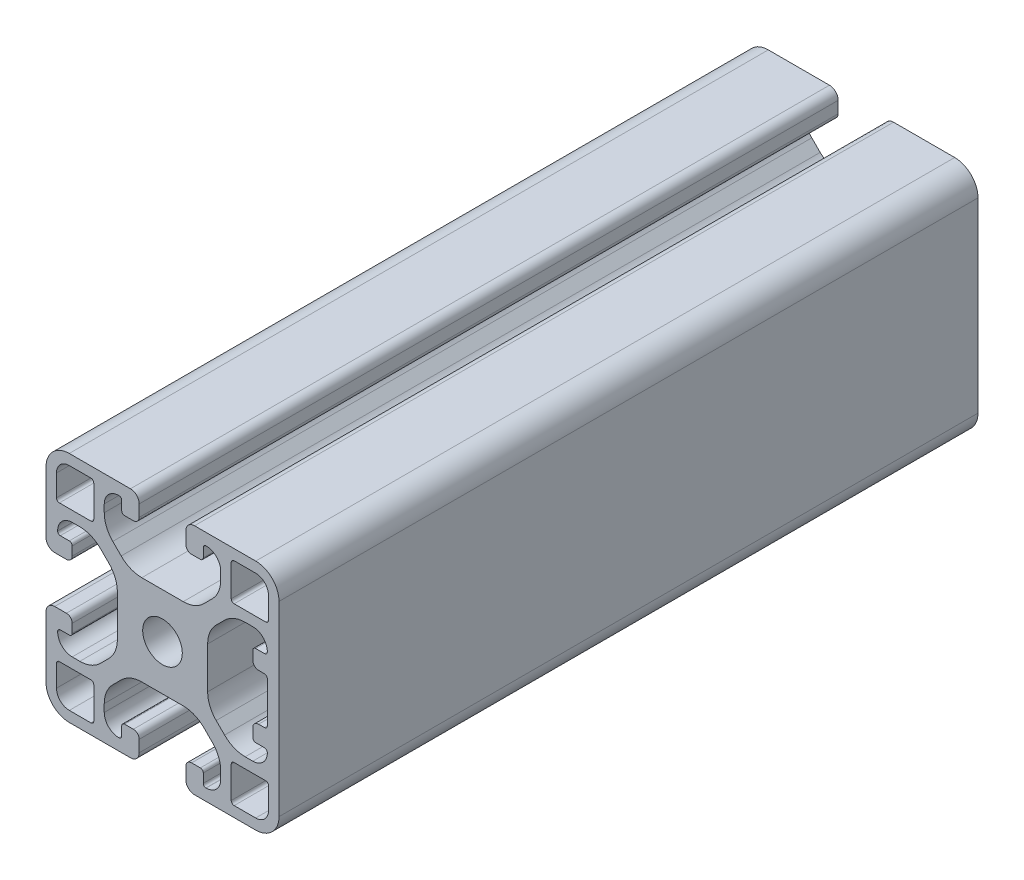
SolidWorks part; units mm, degrees
ref_plane "Piano frontale" through (0, 0, 0) normal (0, 0, 1) x (1, 0, 0)
ref_plane "Piano superiore" through (0, 0, 0) normal (0, 1, 0) x (1, 0, 0)
ref_plane "Piano destro" through (0, 0, 0) normal (1, 0, 0) x (0, 0, -1)
ref_plane "Piano1" through (0, 0, -340) normal (0, 0, -1) x (-1, 0, 0)
sketch "Schizzo1" plane through (0, 0, -340) normal (0, 0, -1) x (-1, 0, 0)
  line L0 (-12.3, -18.2) -> (-16, -18.2)
  line L1 (-18.2, -16) -> (-18.2, -12.3)
  line L2 (-17.7, -11.8) -> (-12.3, -11.8)
  line L3 (-11.8, -12.3) -> (-11.8, -17.7)
  line L4 (-11.8, 17.7) -> (-11.8, 12.3)
  line L5 (-12.3, 11.8) -> (-17.7, 11.8)
  line L6 (-18.2, 12.3) -> (-18.2, 16)
  line L7 (-16, 18.2) -> (-12.3, 18.2)
  line L8 (18.2, 16) -> (18.2, 12.3)
  line L9 (17.7, 11.8) -> (12.3, 11.8)
  line L10 (11.8, 12.3) -> (11.8, 17.7)
  line L11 (12.3, 18.2) -> (16, 18.2)
  line L12 (6.5, -15.5) -> (5, -15.5)
  line L13 (4, -16.5) -> (4, -18.5)
  line L14 (5.5, -20) -> (16, -20)
  line L15 (20, -16) -> (20, -5.5)
  line L16 (18.5, -4) -> (16.5, -4)
  line L17 (15.5, -5) -> (15.5, -6.5)
  line L18 (16, -7) -> (17.55, -7)
  line L19 (18, -7.45) -> (18, -7.5)
  line L20 (15.5, -10) -> (14.1924, -10)
  line L21 (10.6569, -8.5355) -> (9.2145, -7.0931)
  line L22 (7.75, -3.5576) -> (7.75, 3.5576)
  line L23 (9.2145, 7.0931) -> (10.6569, 8.5355)
  line L24 (14.1924, 10) -> (15.5, 10)
  line L25 (18, 7.5) -> (18, 7.45)
  line L26 (17.55, 7) -> (16, 7)
  line L27 (15.5, 6.5) -> (15.5, 5)
  line L28 (16.5, 4) -> (18.5, 4)
  line L29 (20, 5.5) -> (20, 16)
  line L30 (16, 20) -> (5.5, 20)
  line L31 (4, 18.5) -> (4, 16.5)
  line L32 (5, 15.5) -> (6.5, 15.5)
  line L33 (7, 16) -> (7, 17.55)
  line L34 (7.45, 18) -> (7.5, 18)
  line L35 (10, 15.5) -> (10, 14.1924)
  line L36 (8.5355, 10.6569) -> (7.0931, 9.2145)
  line L37 (3.5576, 7.75) -> (-3.5576, 7.75)
  line L38 (-7.0931, 9.2145) -> (-8.5355, 10.6569)
  line L39 (-10, 14.1924) -> (-10, 15.5)
  line L40 (-7.5, 18) -> (-7.45, 18)
  line L41 (-7, 17.55) -> (-7, 16)
  line L42 (-6.5, 15.5) -> (-5, 15.5)
  line L43 (-4, 16.5) -> (-4, 18.5)
  line L44 (-5.5, 20) -> (-16, 20)
  line L45 (-20, 16) -> (-20, -16)
  line L46 (-16, -20) -> (-5.5, -20)
  line L47 (-4, -18.5) -> (-4, -16.5)
  line L48 (-5, -15.5) -> (-6.5, -15.5)
  line L49 (-7, -16) -> (-7, -17.55)
  line L50 (-7.45, -18) -> (-7.5, -18)
  line L51 (-10, -15.5) -> (-10, -14.1924)
  line L52 (-8.5355, -10.6569) -> (-7.0931, -9.2145)
  line L53 (-3.5576, -7.75) -> (3.5576, -7.75)
  line L54 (7.0931, -9.2145) -> (8.5355, -10.6569)
  line L55 (10, -14.1924) -> (10, -15.5)
  line L56 (7.5, -18) -> (7.45, -18)
  line L57 (7, -17.55) -> (7, -16)
  line L58 (18.2, -12.3) -> (18.2, -16)
  line L59 (16, -18.2) -> (12.3, -18.2)
  line L60 (11.8, -17.7) -> (11.8, -12.3)
  line L61 (12.3, -11.8) -> (17.7, -11.8)
  line L62 (-16, 7) -> (-17.5, 7)
  line L63 (-15.5, 10) -> (-14.1924, 10)
  line L64 (-10.6569, 8.5355) -> (-9.2145, 7.0931)
  line L65 (-7.75, 3.5576) -> (-7.75, -3.5576)
  line L66 (-9.2145, -7.0931) -> (-10.6569, -8.5355)
  line L67 (-14.1924, -10) -> (-15.5, -10)
  line L68 (-17.5, -7) -> (-16, -7)
  line L69 (-15.5, -6.5) -> (-15.5, -5)
  line L70 (-16.5, -4) -> (-17.5, -4)
  line L71 (-18, -3.5) -> (-18, 3.5)
  line L72 (-17.5, 4) -> (-16.5, 4)
  line L73 (-15.5, 5) -> (-15.5, 6.5)
  arc A0 (-16, -18.2) -> (-18.2, -16) centre (-16, -16) cw
  arc A1 (-18.2, -12.3) -> (-17.7, -11.8) centre (-17.7, -12.3) cw
  arc A2 (-12.3, -11.8) -> (-11.8, -12.3) centre (-12.3, -12.3) cw
  arc A3 (-11.8, -17.7) -> (-12.3, -18.2) centre (-12.3, -17.7) cw
  arc A4 (-12.3, 18.2) -> (-11.8, 17.7) centre (-12.3, 17.7) cw
  arc A5 (-11.8, 12.3) -> (-12.3, 11.8) centre (-12.3, 12.3) cw
  arc A6 (-17.7, 11.8) -> (-18.2, 12.3) centre (-17.7, 12.3) cw
  arc A7 (-18.2, 16) -> (-16, 18.2) centre (-16, 16) cw
  arc A8 (16, 18.2) -> (18.2, 16) centre (16, 16) cw
  arc A9 (18.2, 12.3) -> (17.7, 11.8) centre (17.7, 12.3) cw
  arc A10 (12.3, 11.8) -> (11.8, 12.3) centre (12.3, 12.3) cw
  arc A11 (11.8, 17.7) -> (12.3, 18.2) centre (12.3, 17.7) cw
  arc A12 (5, -15.5) -> (4, -16.5) centre (5, -16.5) ccw
  arc A13 (4, -18.5) -> (5.5, -20) centre (5.5, -18.5) ccw
  arc A14 (16, -20) -> (20, -16) centre (16, -16) ccw
  arc A15 (20, -5.5) -> (18.5, -4) centre (18.5, -5.5) ccw
  arc A16 (16.5, -4) -> (15.5, -5) centre (16.5, -5) ccw
  arc A17 (15.5, -6.5) -> (16, -7) centre (16, -6.5) ccw
  arc A18 (17.55, -7) -> (18, -7.45) centre (17.55, -7.45) cw
  arc A19 (18, -7.5) -> (15.5, -10) centre (15.5, -7.5) cw
  arc A20 (14.1924, -10) -> (10.6569, -8.5355) centre (14.1924, -5) cw
  arc A21 (9.2145, -7.0931) -> (7.75, -3.5576) centre (12.75, -3.5576) cw
  arc A22 (7.75, 3.5576) -> (9.2145, 7.0931) centre (12.75, 3.5576) cw
  arc A23 (10.6569, 8.5355) -> (14.1924, 10) centre (14.1924, 5) cw
  arc A24 (15.5, 10) -> (18, 7.5) centre (15.5, 7.5) cw
  arc A25 (18, 7.45) -> (17.55, 7) centre (17.55, 7.45) cw
  arc A26 (16, 7) -> (15.5, 6.5) centre (16, 6.5) ccw
  arc A27 (15.5, 5) -> (16.5, 4) centre (16.5, 5) ccw
  arc A28 (18.5, 4) -> (20, 5.5) centre (18.5, 5.5) ccw
  arc A29 (20, 16) -> (16, 20) centre (16, 16) ccw
  arc A30 (5.5, 20) -> (4, 18.5) centre (5.5, 18.5) ccw
  arc A31 (4, 16.5) -> (5, 15.5) centre (5, 16.5) ccw
  arc A32 (6.5, 15.5) -> (7, 16) centre (6.5, 16) ccw
  arc A33 (7, 17.55) -> (7.45, 18) centre (7.45, 17.55) cw
  arc A34 (7.5, 18) -> (10, 15.5) centre (7.5, 15.5) cw
  arc A35 (10, 14.1924) -> (8.5355, 10.6569) centre (5, 14.1924) cw
  arc A36 (7.0931, 9.2145) -> (3.5576, 7.75) centre (3.5576, 12.75) cw
  arc A37 (-3.5576, 7.75) -> (-7.0931, 9.2145) centre (-3.5576, 12.75) cw
  arc A38 (-8.5355, 10.6569) -> (-10, 14.1924) centre (-5, 14.1924) cw
  arc A39 (-10, 15.5) -> (-7.5, 18) centre (-7.5, 15.5) cw
  arc A40 (-7.45, 18) -> (-7, 17.55) centre (-7.45, 17.55) cw
  arc A41 (-7, 16) -> (-6.5, 15.5) centre (-6.5, 16) ccw
  arc A42 (-5, 15.5) -> (-4, 16.5) centre (-5, 16.5) ccw
  arc A43 (-4, 18.5) -> (-5.5, 20) centre (-5.5, 18.5) ccw
  arc A44 (-16, 20) -> (-20, 16) centre (-16, 16) ccw
  arc A45 (-20, -16) -> (-16, -20) centre (-16, -16) ccw
  arc A46 (-5.5, -20) -> (-4, -18.5) centre (-5.5, -18.5) ccw
  arc A47 (-4, -16.5) -> (-5, -15.5) centre (-5, -16.5) ccw
  arc A48 (-6.5, -15.5) -> (-7, -16) centre (-6.5, -16) ccw
  arc A49 (-7, -17.55) -> (-7.45, -18) centre (-7.45, -17.55) cw
  arc A50 (-7.5, -18) -> (-10, -15.5) centre (-7.5, -15.5) cw
  arc A51 (-10, -14.1924) -> (-8.5355, -10.6569) centre (-5, -14.1924) cw
  arc A52 (-7.0931, -9.2145) -> (-3.5576, -7.75) centre (-3.5576, -12.75) cw
  arc A53 (3.5576, -7.75) -> (7.0931, -9.2145) centre (3.5576, -12.75) cw
  arc A54 (8.5355, -10.6569) -> (10, -14.1924) centre (5, -14.1924) cw
  arc A55 (10, -15.5) -> (7.5, -18) centre (7.5, -15.5) cw
  arc A56 (7.45, -18) -> (7, -17.55) centre (7.45, -17.55) cw
  arc A57 (7, -16) -> (6.5, -15.5) centre (6.5, -16) ccw
  arc A58 (17.7, -11.8) -> (18.2, -12.3) centre (17.7, -12.3) cw
  arc A59 (18.2, -16) -> (16, -18.2) centre (16, -16) cw
  arc A60 (12.3, -18.2) -> (11.8, -17.7) centre (12.3, -17.7) cw
  arc A61 (11.8, -12.3) -> (12.3, -11.8) centre (12.3, -12.3) cw
  circle A62 centre (0, 0) radius 3.4
  arc A63 (-15.5, 6.5) -> (-16, 7) centre (-16, 6.5) ccw
  arc A64 (-17.5, 7) -> (-18, 7.5) centre (-17.5, 7.5) cw
  arc A65 (-18, 7.5) -> (-15.5, 10) centre (-15.5, 7.5) cw
  arc A66 (-14.1924, 10) -> (-10.6569, 8.5355) centre (-14.1924, 5) cw
  arc A67 (-9.2145, 7.0931) -> (-7.75, 3.5576) centre (-12.75, 3.5576) cw
  arc A68 (-7.75, -3.5576) -> (-9.2145, -7.0931) centre (-12.75, -3.5576) cw
  arc A69 (-10.6569, -8.5355) -> (-14.1924, -10) centre (-14.1924, -5) cw
  arc A70 (-15.5, -10) -> (-18, -7.5) centre (-15.5, -7.5) cw
  arc A71 (-18, -7.5) -> (-17.5, -7) centre (-17.5, -7.5) cw
  arc A72 (-16, -7) -> (-15.5, -6.5) centre (-16, -6.5) ccw
  arc A73 (-15.5, -5) -> (-16.5, -4) centre (-16.5, -5) ccw
  arc A74 (-17.5, -4) -> (-18, -3.5) centre (-17.5, -3.5) cw
  arc A75 (-18, 3.5) -> (-17.5, 4) centre (-17.5, 3.5) cw
  arc A76 (-16.5, 4) -> (-15.5, 5) centre (-16.5, 5) ccw
extrude "Estrusione-Estrusione1" add sketch "Schizzo1" against normal blind 120
